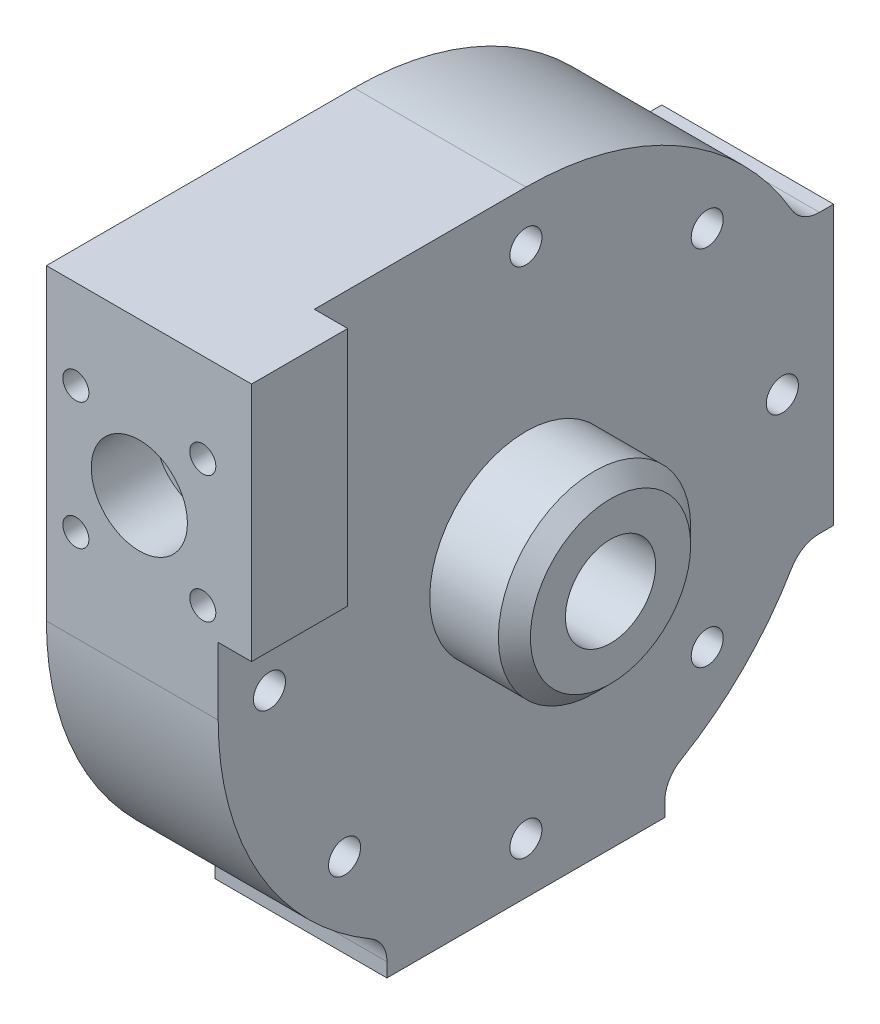
SolidWorks part; units mm, degrees
material "6061 Alloy"
ref_plane "Front Plane" through (0, 0, 0) normal (0, 0, 1) x (1, 0, 0)
ref_plane "Top Plane" through (0, 0, 0) normal (0, 1, 0) x (1, 0, 0)
ref_plane "Right Plane" through (0, 0, 0) normal (1, 0, 0) x (0, 0, -1)
sketch "Sketch1" plane through (0, 0, 0) normal (1, 0, 0) x (0, 0, -1)
  line L0 (-60.96, 0) -> (-60.96, 60.96)
  line L1 (-60.96, 60.96) -> (0, 60.96)
  line L2 (-27.53, -60.96) -> (27.53, -60.96)
  line L3 (27.53, -60.96) -> (27.53, -54.3895)
  line L4 (0, 55) -> (0, -55) construction
  line L5 (-27.53, -60.96) -> (-27.53, -54.3895)
  line L6 (60.96, 27.559) -> (60.96, -27.559)
  line L7 (60.96, -27.559) -> (54.3748, -27.559)
  line L8 (55, 0) -> (-55, 0) construction
  line L9 (60.96, 27.559) -> (54.3748, 27.559)
  arc A1 (-60.96, 0) -> (-27.53, -54.3895) centre (0, 0) ccw
  arc A2 (27.53, -54.3895) -> (54.3748, -27.559) centre (0, 0) ccw
  arc A3 (54.3748, 27.559) -> (0, 60.96) centre (0, 0) ccw
  point P17 (60.96, 0)
extrude "Housing 2" add sketch "Sketch1" along normal blind 44.45 contours L0 L1 A3 L9 L6 L7 A2 L3 L2 L5 A1
sketch "Sketch2" plane through (0, 0, 0) normal (-1, 0, 0) x (0, 0, 1)
  circle A0 centre (0, 0) radius 36.6649
  dimension "D1" = 73.3298
extrude "Impeller Cut" cut sketch "Sketch2" against normal blind 22.4028
sketch "Sketch3" plane through (0, 0, 0) normal (0, 0, 1) x (1, 0, 0)
  line L2 (28.0833, 9.2879) -> (22.4028, 36.6649)
  line L3 (28.0833, 9.2879) -> (28.0833, 0)
  line L4 (44.45, 0) -> (0, 0) construction
  line L7 (22.4028, 36.6649) -> (22.225, 0)
  line L8 (22.225, 0) -> (28.0833, 0)
  dimension "D1" = 12
  dimension "D2" = 9.2879
revolve "Impeller Angle Cut" cut sketch "Sketch3" angle 360 about L8
sketch "Sketch4" plane through (28.0833, 0, 0) normal (-1, 0, 0) x (0, 0, 1)
  circle A0 centre (0, 0) radius 4.826
extrude "Inlet Cut" cut sketch "Sketch4" against normal blind 19.8628
sketch "Sketch5" plane through (44.45, 0, 0) normal (1, 0, 0) x (0, 0, -1)
  circle A1 centre (0, 19.05) radius 1.5875
extrude "Inlet Fastener Bore" [suppressed] cut sketch "Sketch5" against normal blind 6.35
pattern_circular "Inlet Fastener Pattern" [suppressed] count 6 over 360
sketch "Sketch6" plane through (44.45, 0, 0) normal (1, 0, 0) x (0, 0, -1)
  line L0 (-60.96, 60.96) -> (0, 60.96) construction
  circle A0 centre (0, 0) radius 4.826 construction
  circle A1 centre (0, 0) radius 50.8 construction
  circle A2 centre (50.8, 0) radius 3.175
  dimension "D1" = 50.8
  dimension "D3" = 6.35
  dimension "D2" = 60.96
extrude "Fastener Bore" cut sketch "Sketch6" against normal blind 116.84
pattern_circular "Fastener Pattern" count 8 over 360 about axis through (0, 0, 0) along (1, 0, 0) skipping 5 of "Fastener Bore"
sketch "Sketch7" plane through (44.45, 0, 0) normal (1, 0, 0) x (0, 0, -1)
  circle A0 centre (0, 0) radius 19.05
  circle A1 centre (0, 0) radius 100.1143
  dimension "D1" = 38.1
  dimension "D2" = 200.2285
extrude "Mass Reduction Cut" cut sketch "Sketch7" against normal blind 10.414
fillet "Fillet3" [suppressed] radius 5.08
sketch "Sketch8" plane through (0, 0, 60.96) normal (0, 0, 1) x (1, 0, 0)
  line L0 (34.036, 0) -> (34.036, 60.96) construction
  line L1 (0, 60.96) -> (34.036, 60.96)
  line L2 (0, 60.96) -> (0, 10.1635)
  line L3 (0, 10.1635) -> (34.036, 10.1635)
  line L4 (34.036, 60.96) -> (34.036, 10.1635)
extrude "Discharge Cut" [suppressed] cut sketch "Sketch8" against normal blind 2.54
fillet "Fillet4" [suppressed] radius 5.08
sketch "Sketch9" [suppressed] plane through (0, 0, 58.42) normal (0, 0, 1) x (1, 0, 0)
  circle A0 centre (19.6343, 36.5011) radius 2.54
extrude "Discharge Bore" [suppressed] cut sketch "Sketch9" against normal blind 50.038
sketch "Sketch11" plane through (44.45, 0, 0) normal (1, 0, 0) x (0, 0, -1)
  circle A0 centre (0, 0) radius 19.05
  circle A1 centre (0, 0) radius 4.826
extrude "Boss-Extrude1" add sketch "Sketch11" along normal blind 6.35
sketch "Sketch12" [suppressed] plane through (56.896, 0, 0) normal (1, 0, 0) x (0, 0, -1)
  circle A0 centre (19.976, 0) radius 3.175
extrude "Cut-Extrude1" [suppressed] cut sketch "Sketch12" against normal blind 19.05
pattern_circular "CirPattern1" [suppressed] count 6 over 360
fillet "Fillet6" [suppressed] radius 2.54
sketch "Sketch13" [suppressed] plane through (0, 0, 58.42) normal (0, 0, 1) x (1, 0, 0)
  circle A0 centre (19.6343, 36.5011) radius 9.525
extrude "Cut-Extrude2" [suppressed] cut sketch "Sketch13" against normal blind 25.4
sketch "Sketch14" plane through (0, 0, 0) normal (0, 0, 1) x (1, 0, 0)
  line L0 (0, 0) -> (0, 60.96) construction
  line L1 (34.036, 60.96) -> (0, 60.96) construction
  circle A0 centre (18.415, 30.734) radius 2.3813
  dimension "D1" = 4.7625
  dimension "D2" = 18.415
  dimension "1.0" = 30.226
extrude "Cut-Extrude3" cut sketch "Sketch14" along normal blind 99.06
sketch "Sketch15" plane through (0, 0, 60.96) normal (0, 0, 1) x (1, 0, 0)
  circle A0 centre (18.415, 30.734) radius 9.525
extrude "Cut-Extrude4" cut sketch "Sketch15" against normal blind 25.4
sketch "Sketch16" plane through (0, 0, 35.56) normal (0, 0, 1) x (1, 0, 0)
  circle A0 centre (18.415, 30.734) radius 9.525
  circle A1 centre (18.415, 30.734) radius 6.35
extrude "Boss-Extrude2" add sketch "Sketch16" along normal blind 12.7
sketch "Sketch18" plane through (0, 0, 60.96) normal (0, 0, 1) x (1, 0, 0)
  line L0 (0, 0) -> (0, 60.96) construction
  line L1 (34.036, 60.96) -> (40.64, 60.96)
  line L2 (34.036, 60.96) -> (34.036, 13.335)
  line L3 (34.036, 13.335) -> (40.64, 13.335)
  line L4 (40.64, 60.96) -> (40.64, 13.335)
  dimension "D1" = 40.64
  dimension "D2" = 47.625
extrude "Boss-Extrude3" add sketch "Sketch18" against normal blind 19.05
sketch "Sketch19" plane through (0, 0, 60.96) normal (0, 0, 1) x (1, 0, 0)
  line L1 (30.9874, 18.1616) -> (18.415, 30.734) construction
  line L2 (18.415, 30.734) -> (18.415, 60.96) construction
  line L3 (40.64, 60.96) -> (0, 60.96) construction
  circle A1 centre (30.9874, 18.1616) radius 2.5781
  circle A2 centre (18.415, 30.734) radius 9.525 construction
  dimension "D3" = 5.1562
  dimension "D1" = 17.78
  dimension "D2" = 135
extrude "Cut-Extrude5" cut sketch "Sketch19" against normal blind 17.78
pattern_circular "CirPattern2" count 4 over 360 about axis through (18.415, 30.734, 0) along (0, 0, 1) of "Cut-Extrude5"
fillet "Fillet8" [suppressed] radius 2.54
ref_plane "Plane1" [suppressed] through (34.036, -60.96, 27.53) normal (0, 0, -1) x (-1, 0, 0)
ref_plane "Plane2" [suppressed] through (34.036, -60.96, -27.53) normal (0, 0, -1) x (-1, 0, 0)
fillet "Fillet9" radius 6.35 4 edges at (17.018, -27.559, -54.3748) (17.018, 27.559, -54.3748) (17.018, -54.3895, -27.53) (17.018, -54.3895, 27.53)
sketch "Sketch20" plane through (0, 60.96, 0) normal (0, 1, 0) x (1, 0, 0)
  circle A0 centre (19.8775, -40.3269) radius 0.6493
extrude "Cut-Extrude6" [suppressed] cut sketch "Sketch20" against normal blind 51.562
sketch "Sketch21" [suppressed] plane through (0, 60.96, 0) normal (0, 1, 0) x (1, 0, 0)
  circle A0 centre (19.8775, -40.3269) radius 4.7625
extrude "Cut-Extrude7" [suppressed] cut sketch "Sketch21" against normal blind 6.35
sketch "Sketch22" plane through (50.8, 0, 0) normal (1, 0, 0) x (0, 0, -1)
  circle A0 centre (0, 0) radius 8.9281
  dimension "D1" = 17.8562
extrude "Cut-Extrude8" cut sketch "Sketch22" against normal blind 17.78
sketch "Sketch23" [suppressed] plane through (0, 60.96, 0) normal (0, 1, 0) x (1, 0, 0)
  line L0 (0, 0) -> (34.036, 0) construction
chamfer "Chamfer1" distance 3.175 angle 45 1 edges at (50.8, 0, -19.05)
